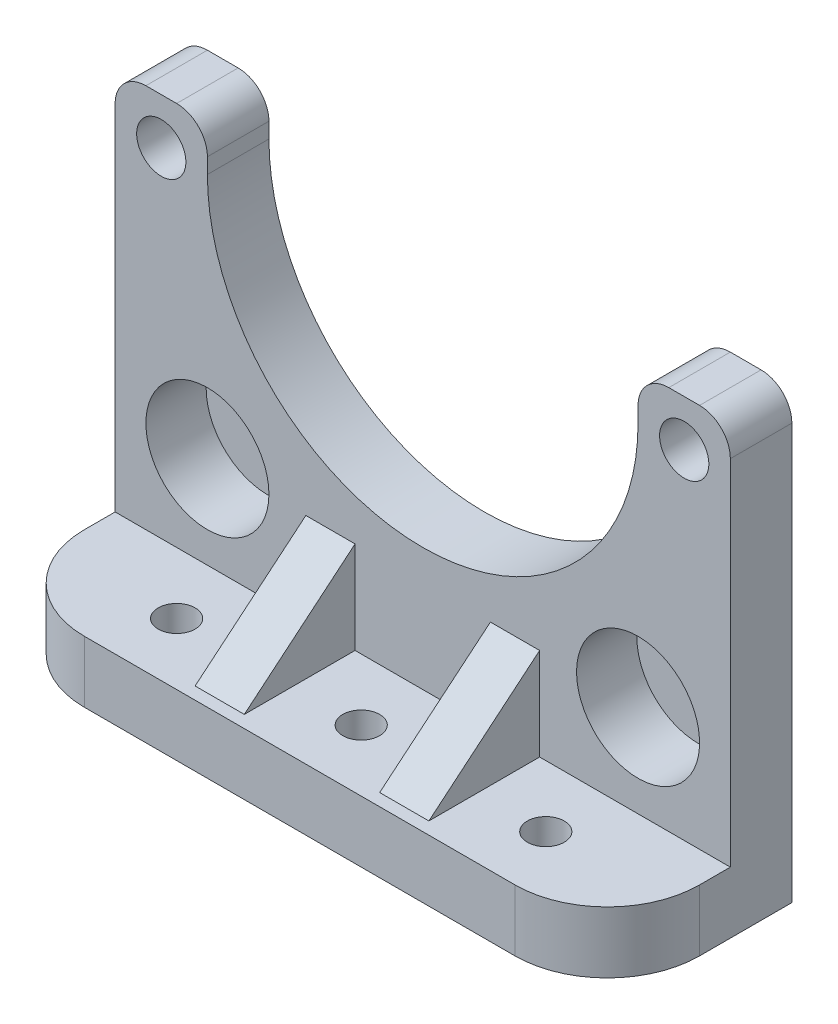
SolidWorks part; units mm, degrees
ref_plane "Front Plane" through (0, 0, 0) normal (0, 0, 1) x (1, 0, 0)
ref_plane "Top Plane" through (0, 0, 0) normal (0, 1, 0) x (1, 0, 0)
ref_plane "Right Plane" through (0, 0, 0) normal (1, 0, 0) x (0, 0, -1)
sketch "Sketch1" plane through (0, 0, 0) normal (0, 0, 1) x (1, 0, 0)
  line L1 (0, 0) -> (100, 0)
  line L2 (0, 0) -> (0, 72.5)
  line L3 (0, 72.5) -> (100, 72.5)
  line L4 (100, 0) -> (100, 72.5)
  dimension "D1" = 72.5
  dimension "D2" = 100
extrude "Boss-Extrude1" add sketch "Sketch1" along normal blind 10
sketch "Sketch2" plane through (0, 0, 10) normal (0, 0, 1) x (1, 0, 0)
  line L1 (50, 72.5) -> (50, 0) construction
  line L3 (100, 72.5) -> (0, 72.5) construction
  line L4 (0, 0) -> (100, 0) construction
  line L7 (85, 65) -> (85, 72.5)
  line L8 (85, 72.5) -> (15, 72.5)
  line L9 (15, 65) -> (15, 72.5)
  arc A0 (15, 65) -> (85, 65) centre (50, 65) ccw
  dimension "D1" = 65
  dimension "D2" = 35
extrude "Cut-Extrude1" cut sketch "Sketch2" against normal up to surface (10 mm away) up to face at (50, 36.25, 0)
sketch "Sketch3" plane through (0, 0, 10) normal (0, 0, 1) x (1, 0, 0)
  line L0 (100, 0) -> (100, 72.5) construction
  line L1 (0, 0) -> (100, 0)
  line L2 (0, 0) -> (0, 10)
  line L3 (0, 10) -> (100, 10)
  line L4 (100, 0) -> (100, 10)
  dimension "D1" = 10
extrude "feet" add sketch "Sketch3" along normal blind 20
sketch "Sketch4" plane through (0, 0, 0) normal (0, -1, 0) x (1, 0, 0)
  line L2 (50, 30) -> (50, 0) construction
  line L3 (0, 30) -> (100, 30) construction
  line L4 (0, 0) -> (100, 0) construction
  circle A0 centre (20, 20) radius 3
  circle A1 centre (80, 20) radius 3
  circle A2 centre (50, 20) radius 3
  dimension "D1" = 6
  dimension "D2" = 30
  dimension "D3" = 30
  dimension "D6" = 20
extrude "feet-hole" cut sketch "Sketch4" against normal up to surface (10 mm away) up to face at (62.5, 10, 25)
sketch "Sketch5" plane through (0, 0, 10) normal (0, 0, 1) x (1, 0, 0)
  line L0 (50, 30) -> (50, 65) construction
  line L1 (7.5, 72.5) -> (7.5, 49.9689) construction
  line L2 (15, 72.5) -> (0, 72.5) construction
  line L3 (-11.3931, 65) -> (60.2155, 65) construction
  line L4 (0, 72.5) -> (0, 10) construction
  line L5 (100, 10) -> (0, 10) construction
  arc A0 (15, 65) -> (85, 65) centre (50, 65) ccw construction
  circle A1 centre (7.5, 65) radius 4
  circle A2 centre (92.5, 65) radius 4
  circle A3 centre (15, 25) radius 10
  circle A4 centre (85, 25) radius 10
  dimension "D1" = 20
  dimension "D3" = 15
  dimension "D2" = 15
sketch "Sketch6" plane through (0, 0, 10) normal (0, 0, 1) x (1, 0, 0)
  line L0 (100, 10) -> (0, 10) construction
  line L1 (31, 10) -> (39, 10)
  line L2 (31, 10) -> (31, 25)
  line L3 (31, 25) -> (39, 25)
  line L4 (39, 10) -> (39, 25)
  line L5 (50, 30) -> (50, 65) construction
  line L6 (50, 65) -> (50, -5.7532) construction
  line L7 (61, 10) -> (61, 25)
  line L8 (69, 25) -> (61, 25)
  line L9 (69, 10) -> (69, 25)
  line L10 (69, 10) -> (61, 10)
  dimension "D1" = 8
  dimension "D2" = 15
  dimension "D3" = 11
extrude "Boss-Extrude2" add sketch "Sketch6" along normal offset from surface (18 mm away) 2 up to face at (50, 5, 30)
sketch "Sketch7" plane through (31, 0, 0) normal (-1, 0, 0) x (0, 0, 1)
  line L0 (10, 25) -> (28, 10)
  line L1 (28, 10) -> (10, 10) construction
  line L2 (28, 10) -> (28, 25) construction
  line L3 (28, 10) -> (28, 25)
  line L4 (28, 25) -> (10, 25)
extrude "Cut-Extrude2" cut sketch "Sketch7" against normal through all
extrude "Cut-Extrude3" cut sketch "Sketch5" against normal offset from surface (9.8 mm away) 0.2 up to face at (50, 48.125, 0)
fillet "Fillet1" radius 5 4 edges at (0, 72.5, 5) (15, 72.5, 5) (85, 72.5, 5) (100, 72.5, 5)
fillet "Fillet2" radius 15 2 edges at (0, 5, 30) (100, 5, 30)
